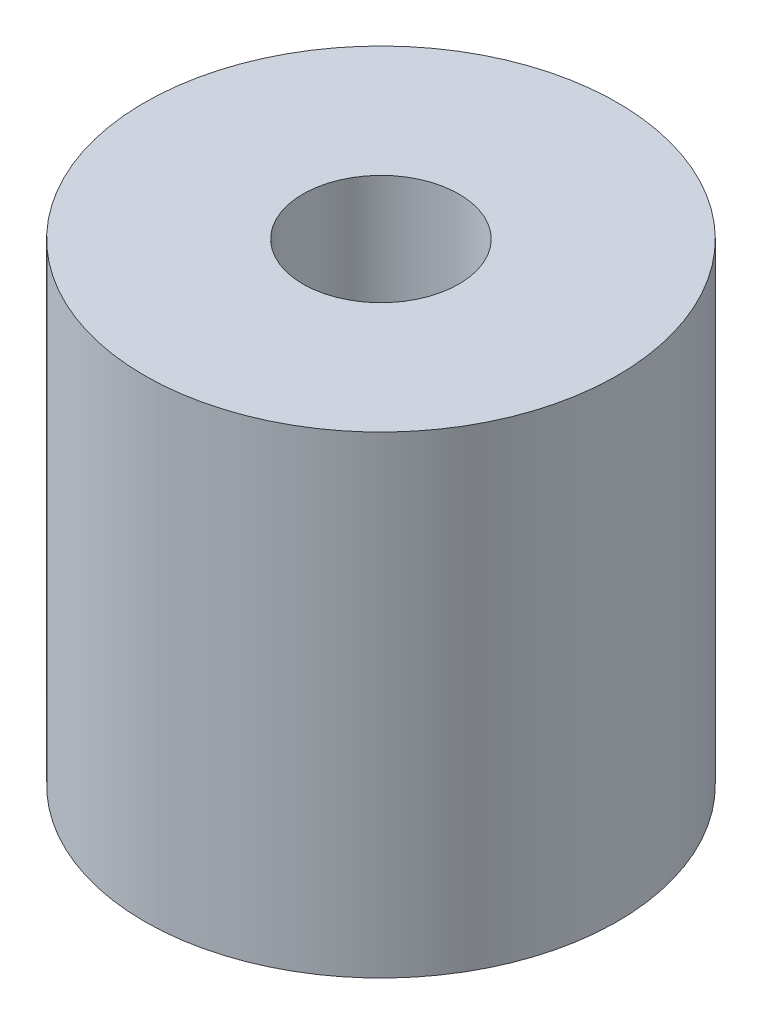
SolidWorks part; units mm, degrees
material "5052-H34"
ref_plane "正面" through (0, 0, 0) normal (0, 0, 1) x (1, 0, 0)
ref_plane "平面" through (0, 0, 0) normal (0, 1, 0) x (1, 0, 0)
ref_plane "右側面" through (0, 0, 0) normal (1, 0, 0) x (0, 0, -1)
sketch "ｽｹｯﾁ1" plane through (0, 0, 0) normal (0, 1, 0) x (1, 0, 0)
  circle A0 centre (0, 0) radius 1.65
  circle A1 centre (0, 0) radius 5
  dimension "D1" = 3.3
  dimension "D2" = 10
extrude "ﾎﾞｽ - 押し出し1" add sketch "ｽｹｯﾁ1" along normal blind 10
